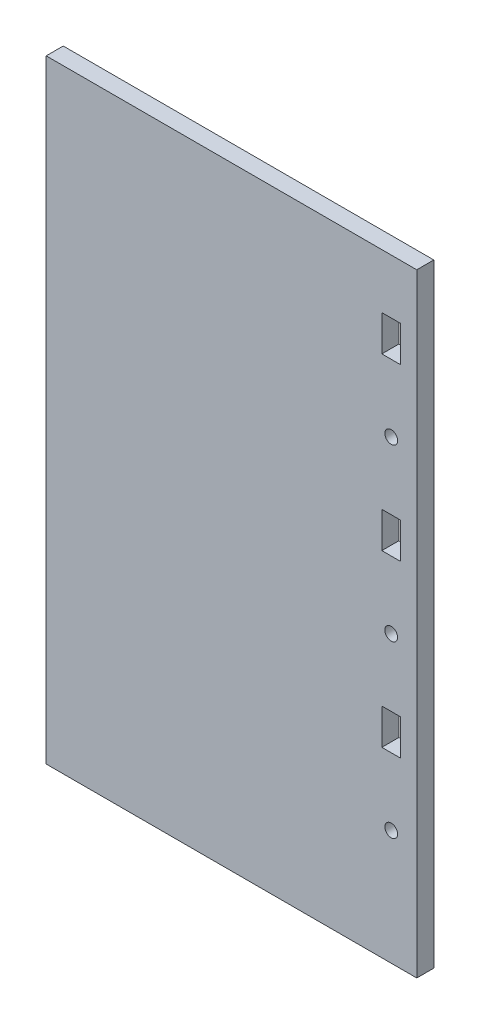
SolidWorks part; units mm, degrees
ref_plane "前视基准面" through (0, 0, 0) normal (0, 0, 1) x (1, 0, 0)
ref_plane "上视基准面" through (0, 0, 0) normal (0, 1, 0) x (1, 0, 0)
ref_plane "右视基准面" through (0, 0, 0) normal (1, 0, 0) x (0, 0, -1)
sketch "草图1" plane through (0, 0, 0) normal (0, 0, 1) x (1, 0, 0)
  line L5 (-43.5, -50) -> (43.5, -50) construction
  line L7 (43.5, -50) -> (43.5, -150)
  line L10 (-43.5, -50) -> (-43.5, -150)
  line L12 (-43.5, -150) -> (43.5, -150) construction
  line L14 (-43.5, -150) -> (-43.5, -154)
  line L15 (-43.5, -154) -> (43.5, -154)
  line L16 (43.5, -154) -> (43.5, -150)
  line L17 (-43.5, -50) -> (43.5, -154) construction
  line L18 (37.5, -147) -> (37.5, -153) construction
  line L19 (37.5, -67) -> (37.5, -147) construction
  line L20 (35.3, -122.8) -> (39.7, -122.8)
  line L21 (35.3, -122.8) -> (35.3, -131.2)
  line L22 (35.3, -131.2) -> (39.7, -131.2)
  line L23 (39.7, -122.8) -> (39.7, -131.2)
  line L24 (35.3, -122.8) -> (39.7, -131.2) construction
  line L25 (35.3, -131.2) -> (39.7, -122.8) construction
  line L26 (37.5, -107) -> (29.7481, -107) construction
  line L27 (39.7, -91.2) -> (39.7, -82.8)
  line L28 (35.3, -82.8) -> (39.7, -82.8)
  line L29 (35.3, -91.2) -> (35.3, -82.8)
  line L30 (35.3, -91.2) -> (39.7, -91.2)
  line L31 (-37.5, -102) -> (-29.7481, -102) construction
  line L32 (-43.5, -50) -> (-43.5, -30)
  line L33 (-43.5, -30) -> (43.5, -30)
  line L34 (43.5, -30) -> (43.5, -50)
  line L35 (-37.5, -142) -> (-37.5, -148) construction
  line L36 (-43.5, -142) -> (-37.5, -142) construction
  line L45 (37.5, -147) -> (-37.5, -67) construction
  line L46 (0, -107) -> (5.2248, -107) construction
  line L47 (0, -102) -> (7.1279, -102) construction
  line L48 (37.5, -67) -> (40.1693, -67) construction
  line L49 (35.3, -51.2) -> (39.7, -51.2)
  line L50 (35.3, -42.8) -> (35.3, -51.2)
  line L51 (35.3, -42.8) -> (39.7, -42.8)
  line L52 (39.7, -42.8) -> (39.7, -51.2)
  circle A0 centre (37.5, -147) radius 1.5
  circle A1 centre (37.5, -67) radius 1.5
  circle A4 centre (0, -62) radius 2 construction
  circle A5 centre (37.5, -107) radius 1.5
  point P7 (37.5, -127)
  point P38 (0, 0)
  point P39 (0, 0)
  point P43 (52.5387, -164.6518)
  point P46 (52.9666, -164.0482)
  dimension "D1" = 20
  dimension "D4" = 80
  dimension "D5" = 87
  dimension "D2" = 4.4
  dimension "D3" = 8.4
extrude "凸台-拉伸1" add sketch "草图1" along normal blind 4
sketch "草图2" plane through (0, 0, 4) normal (0, 0, 1) x (1, 0, 0)
  line L5 (-43.5, -154) -> (43.5, -154)
  line L6 (-43.5, -154) -> (-43.5, -174)
  line L7 (-43.5, -174) -> (43.5, -174)
  line L8 (43.5, -154) -> (43.5, -174)
extrude "凸台-拉伸2" add sketch "草图2" against normal blind 4
